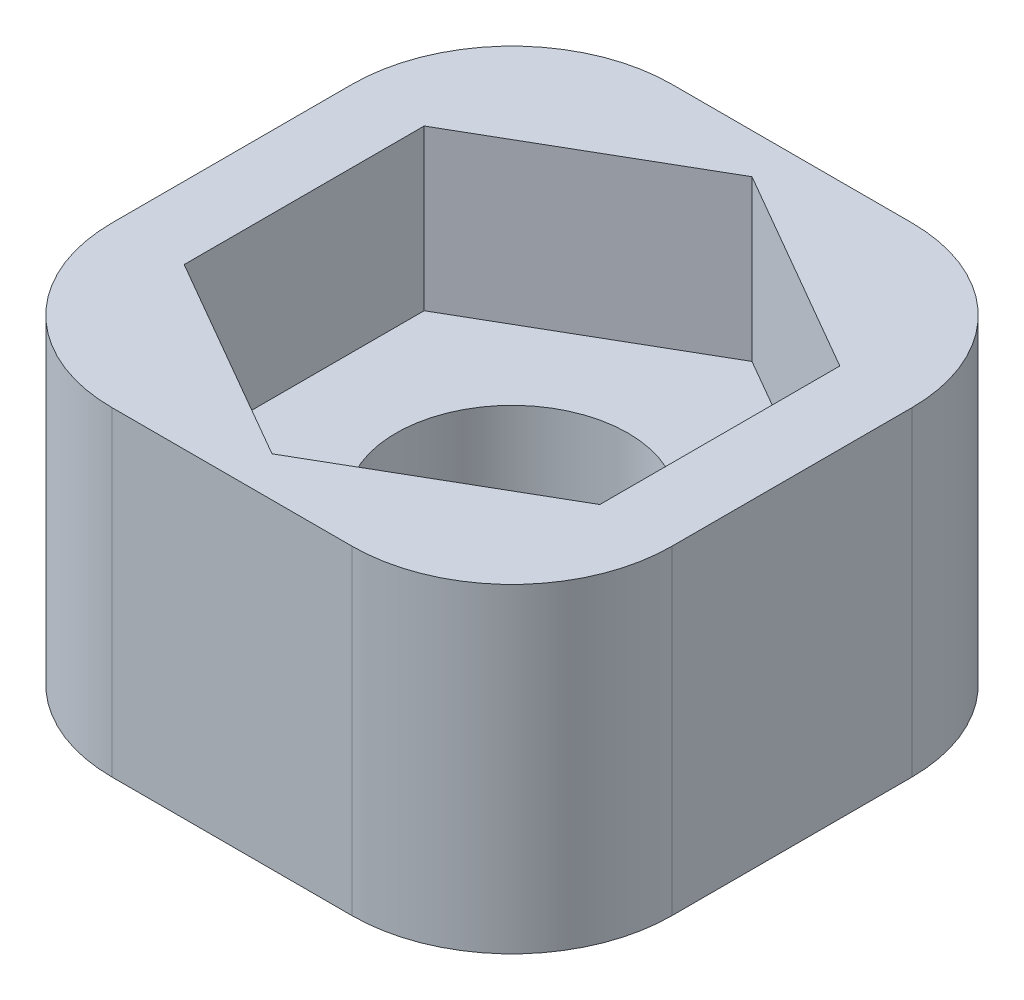
SolidWorks part; units mm, degrees
ref_plane "Front Plane" through (0, 0, 0) normal (0, 0, 1) x (1, 0, 0)
ref_plane "Top Plane" through (0, 0, 0) normal (0, 1, 0) x (1, 0, 0)
ref_plane "Right Plane" through (0, 0, 0) normal (1, 0, 0) x (0, 0, -1)
sketch "Sketch1" plane through (0, 0, 0) normal (0, 1, 0) x (1, 0, 0)
  line L1 (-3.5, -3.5) -> (3.5, -3.5)
  line L2 (-3.5, -3.5) -> (-3.5, 3.5)
  line L3 (-3.5, 3.5) -> (3.5, 3.5)
  line L4 (3.5, -3.5) -> (3.5, 3.5)
  line L5 (-3.5, -3.5) -> (3.5, 3.5) construction
  line L6 (-3.5, 3.5) -> (3.5, -3.5) construction
  point P0 (0, 0)
  dimension "D1" = 7
  dimension "D2" = 7
extrude "Boss-Extrude1" add sketch "Sketch1" along normal blind 4
sketch "Sketch2" plane through (0, 4, 0) normal (0, 1, 0) x (1, 0, 0)
  line L0 (-3.5, 0) -> (3.5, 0) construction
  line L1 (2.5981, -1.5) -> (2.5981, 1.5)
  line L2 (2.5981, 1.5) -> (0, 3)
  line L3 (0, 3) -> (-2.5981, 1.5)
  line L4 (-2.5981, 1.5) -> (-2.5981, -1.5)
  line L5 (-2.5981, -1.5) -> (0, -3)
  line L6 (0, -3) -> (2.5981, -1.5)
  line L7 (-3.5, 3.5) -> (-3.5, -3.5) construction
  line L8 (3.5, -3.5) -> (3.5, 3.5) construction
  circle A1 centre (0, 0) radius 2.5981 construction
  dimension "D1" = 3
extrude "Cut-Extrude1" cut sketch "Sketch2" against normal blind 2
sketch "Sketch4" plane through (0, 2, 0) normal (0, 1, 0) x (1, 0, 0)
  circle A0 centre (0, 0) radius 1.45
  dimension "D1" = 2.9
extrude "Cut-Extrude2" cut sketch "Sketch4" against normal up to surface (2 mm away) up to face at (0, 0, 0)
fillet "Fillet1" radius 2 4 edges at (3.5, 2, 3.5) (-3.5, 2, 3.5) (-3.5, 2, -3.5) (3.5, 2, -3.5)
equation "\"D2@Sketch1\"=\"D1@Sketch1\""
